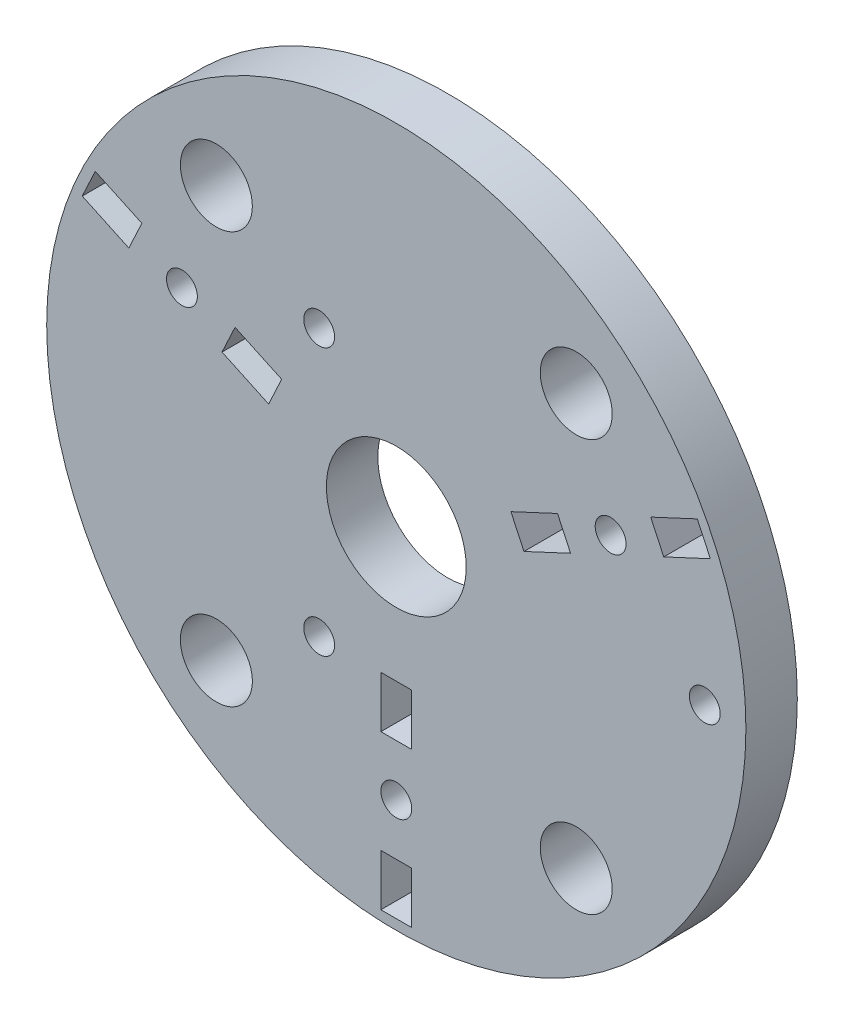
SolidWorks part; units mm, degrees
ref_plane "Front Plane" through (0, 0, 0) normal (0, 0, 1) x (1, 0, 0)
ref_plane "Top Plane" through (0, 0, 0) normal (0, 1, 0) x (1, 0, 0)
ref_plane "Right Plane" through (0, 0, 0) normal (1, 0, 0) x (0, 0, -1)
sketch "Sketch1" plane through (0, 0, 0) normal (0, 0, 1) x (1, 0, 0)
  line L0 (0, 0) -> (34, 0) construction
  line L5 (0, 0) -> (0, -23) construction
  line L10 (0, 0) -> (30.8145, 14.369) construction
  line L11 (0, 0) -> (-30.8145, 14.369) construction
  circle A0 centre (0, 0) radius 34
  circle A1 centre (15, 0) radius 1.5 construction
  circle A2 centre (30, 0) radius 1.5
  circle A3 centre (-7.5, -12.9904) radius 1.5
  circle A4 centre (-15, -25.9808) radius 1.5 construction
  circle A5 centre (-7.5, 12.9904) radius 1.5
  circle A6 centre (-15, 25.9808) radius 1.5 construction
  circle A7 centre (0, 0) radius 6.8
  circle A8 centre (-17.5, 20) radius 3.5
  circle A9 centre (17.5, 20) radius 3.5
  circle A10 centre (-17.5, -20) radius 3.5
  circle A11 centre (17.5, -20) radius 3.5
  circle A12 centre (0, 0) radius 23 construction
  point P23 (0, 0)
  line B0 (16.3135, 7.6071) -> (25.3766, 11.8333) construction
  line B1 (15.6796, 8.9666) -> (11.1481, 6.8535)
  line B2 (15.6796, 8.9666) -> (16.9475, 6.2477)
  line B3 (16.9475, 6.2477) -> (12.4159, 4.1346)
  line B4 (11.1481, 6.8535) -> (12.4159, 4.1346)
  line B5 (24.7427, 13.1928) -> (29.2742, 15.3059)
  line B6 (24.7427, 13.1928) -> (26.0105, 10.4738)
  line B7 (26.0105, 10.4738) -> (30.5421, 12.5869)
  line B8 (29.2742, 15.3059) -> (30.5421, 12.5869)
  circle B9 centre (20.8451, 9.7202) radius 1.5
  line B10 (-16.3135, 7.6071) -> (-25.3766, 11.8333) construction
  line B11 (-16.9475, 6.2477) -> (-12.4159, 4.1346)
  line B12 (-16.9475, 6.2477) -> (-15.6796, 8.9666)
  line B13 (-15.6796, 8.9666) -> (-11.1481, 6.8535)
  line B14 (-12.4159, 4.1346) -> (-11.1481, 6.8535)
  line B15 (-26.0105, 10.4738) -> (-30.5421, 12.5869)
  line B16 (-26.0105, 10.4738) -> (-24.7427, 13.1928)
  line B17 (-24.7427, 13.1928) -> (-29.2742, 15.3059)
  line B18 (-30.5421, 12.5869) -> (-29.2742, 15.3059)
  circle B19 centre (-20.8451, 9.7202) radius 1.5
  line B20 (0, -28) -> (0, -18) construction
  line B21 (-1.5, -28) -> (-1.5, -33)
  line B22 (-1.5, -28) -> (1.5, -28)
  line B23 (1.5, -28) -> (1.5, -33)
  line B24 (-1.5, -33) -> (1.5, -33)
  line B25 (-1.5, -18) -> (-1.5, -13)
  line B26 (-1.5, -18) -> (1.5, -18)
  line B27 (1.5, -18) -> (1.5, -13)
  line B28 (-1.5, -13) -> (1.5, -13)
  circle B29 centre (0, -23) radius 1.5
  dimension "D1" = 68
  dimension "D3" = 3
  dimension "D2" = 13.6
  dimension "D9" = 7
  dimension "D4" = 15
  dimension "D5" = 15
  dimension "D7" = 20
  dimension "D8" = 115
  dimension "D10" = 115
  dimension "D11" = 23
  dimension "D12" = 90
  dimension "D13" = 17.5
  dimension "D6" = 3
sketch_block_instance "Trou M3 plots 3mm-1"
sketch_block "Trou M3 plots 3mm" parameters "D2"=3, "D1"=3, "D3"=5, "D4"=10
sketch_block_instance "Trou M3 plots 3mm-2"
sketch_block_instance "Trou M3 plots 3mm-3"
extrude "Boss-Extrude1" add sketch "Sketch1" along normal blind 5
